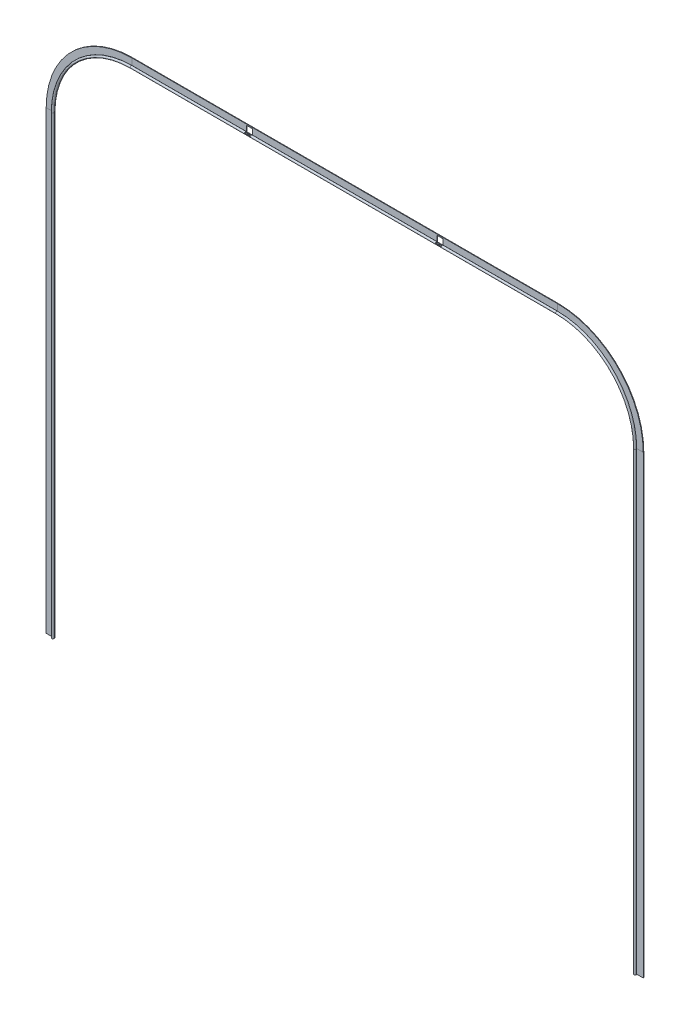
SolidWorks part; units mm, degrees
ref_plane "Front Plane" through (0, 0, 0) normal (0, 0, 1) x (1, 0, 0)
ref_plane "Top Plane" through (0, 0, 0) normal (0, 1, 0) x (1, 0, 0)
ref_plane "Right Plane" through (0, 0, 0) normal (1, 0, 0) x (0, 0, -1)
sketch "Sketch1" plane through (0, 0, 0) normal (0, 0, 1) x (1, 0, 0)
  line L0 (0, 0) -> (0, 1670)
  line L1 (285, 1955) -> (1845, 1955)
  line L2 (2130, 1670) -> (2130, 0)
  arc A0 (0, 1670) -> (285, 1955) centre (285, 1670) cw
  arc A1 (1845, 1955) -> (2130, 1670) centre (1845, 1670) cw
  dimension "D2" = 285
  dimension "D1" = 1670
  dimension "D3" = 1560
sketch "Sketch2" plane through (0, 0, 0) normal (0, 1, 0) x (1, 0, 0)
  line L0 (0, 0) -> (0, -2)
  line L5 (-6, -2) -> (-30, -2)
  line L6 (-30, -2) -> (-30, 0)
  line L7 (-30, 0) -> (0, 0)
  arc A0 (-6, -2) -> (0, -2) centre (-3, -4.6458) ccw
  circle A1 centre (-3, -4.6458) radius 2
  point P5 (0, -2)
  point P6 (0, 0)
  point P10 (-6.3541, -2)
  dimension "D2" = 4
  dimension "D4" = 4
  dimension "D1" = 30
  dimension "D3" = 2
  dimension "D5" = 6
sweep "Sweep1" add profiles "Sketch2" path "Sketch1"
sketch "Sketch3" plane through (0, 0, 0) normal (0, 0, -1) x (-1, 0, 0)
  line L0 (-1845, 1955) -> (-1845, 1985) construction
  line L1 (-1426, 1981) -> (-1404, 1981)
  line L2 (-1426, 1981) -> (-1426, 1959)
  line L3 (-1426, 1959) -> (-1404, 1959)
  line L4 (-1404, 1981) -> (-1404, 1959)
  line L5 (-726, 1981) -> (-704, 1981)
  line L6 (-726, 1981) -> (-726, 1959)
  line L7 (-726, 1959) -> (-704, 1959)
  line L8 (-704, 1981) -> (-704, 1959)
  line L9 (-285, 1955) -> (-285, 1985) construction
  point P12 (-1845, 1970)
  point P13 (-1426, 1970)
  dimension "D1" = 22
  dimension "D2" = 419
  dimension "D3" = 419
extrude "Cut-Extrude1" cut sketch "Sketch3" against normal through all
